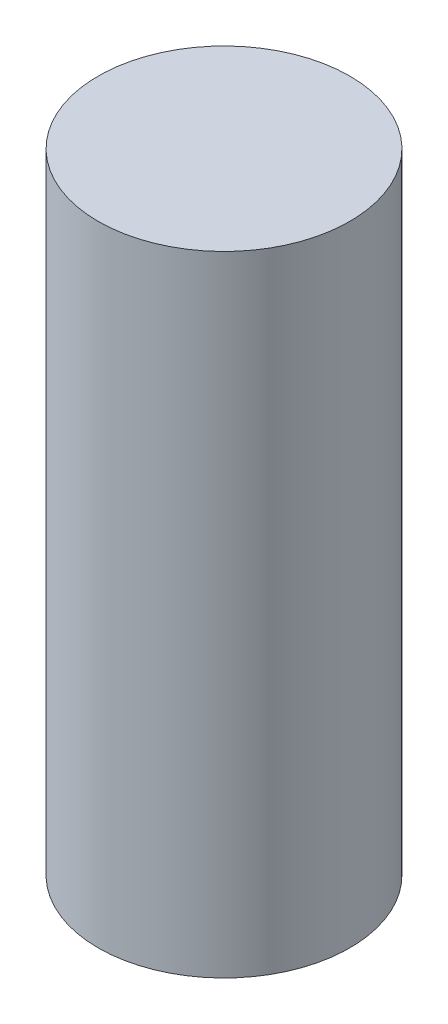
SolidWorks part; units mm, degrees
ref_plane "Front Plane" through (0, 0, 0) normal (0, 0, 1) x (1, 0, 0)
ref_plane "Top Plane" through (0, 0, 0) normal (0, 1, 0) x (1, 0, 0)
ref_plane "Right Plane" through (0, 0, 0) normal (1, 0, 0) x (0, 0, -1)
sketch "Sketch1" plane through (0, 0, 0) normal (0, 1, 0) x (1, 0, 0)
  circle A0 centre (0, 0) radius 609.6
  point P3 (0, -609.6)
extrude "Boss-Extrude1" add sketch "Sketch1" along normal blind 3048
ref_plane "Plane2" through (0, 0, 609.6) normal (0, 0, 1) x (1, 0, 0)
sketch "Sketch3" plane through (0, 0, 609.6) normal (0, 0, 1) x (1, 0, 0)
  line L0 (0, 0) -> (3021.7364, 3048)
  line L1 (3021.7364, 3048) -> (0, 3048)
  line L2 (609.6, 3048) -> (-609.6, 3048) construction
  line L3 (0, 3048) -> (0, 0)
  dimension "D1" = 3021.7364
